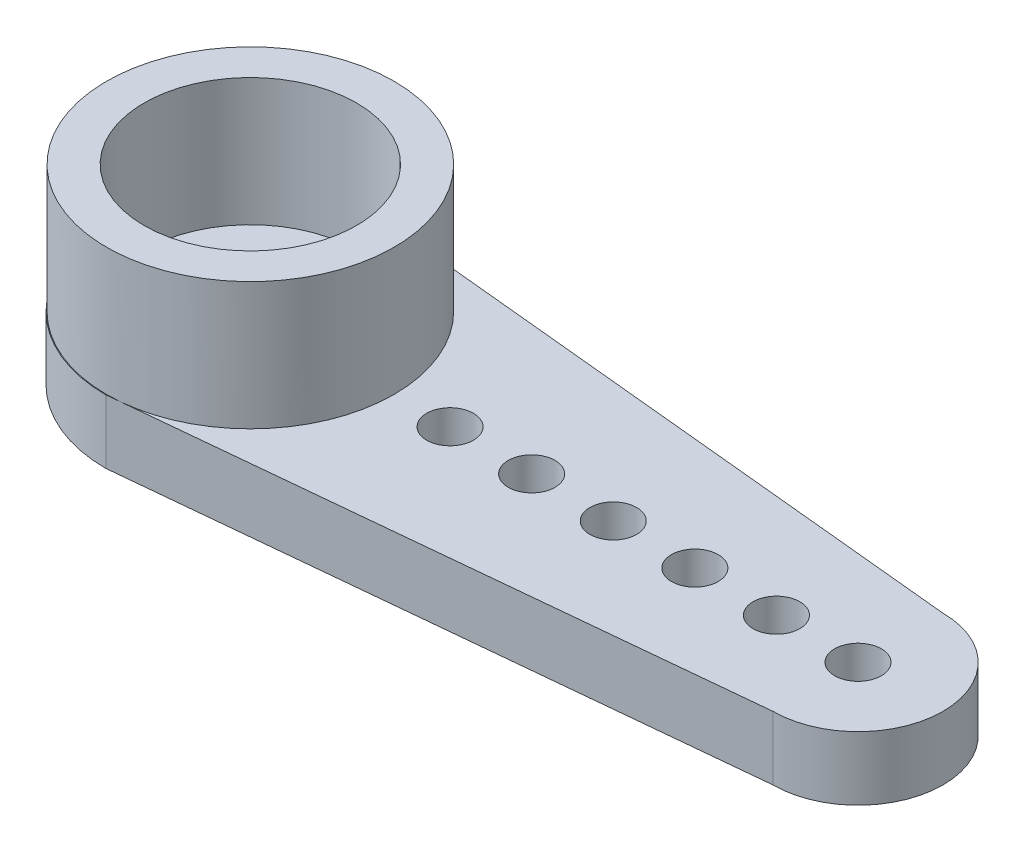
SolidWorks part; units mm, degrees
ref_plane "Front Plane" through (0, 0, 0) normal (0, 0, 1) x (1, 0, 0)
ref_plane "Top Plane" through (0, 0, 0) normal (0, 1, 0) x (1, 0, 0)
ref_plane "Right Plane" through (0, 0, 0) normal (1, 0, 0) x (0, 0, -1)
sketch "Sketch1" plane through (0, 0, 0) normal (0, 1, 0) x (1, 0, 0)
  line L1 (0, 3.4) -> (14.3, 2)
  line L2 (0, -3.4) -> (14.3, -2)
  arc A0 (0.6594, 3.3354) -> (0.6594, -3.3354) centre (0, 0) ccw
  arc A1 (14.3, -2) -> (14.3, 2) centre (14.3, 0) ccw
  dimension "D1" = 6.8
  dimension "D2" = 4
extrude "Boss-Extrude1" add sketch "Sketch1" along normal blind 1.5 contours L2 A1 L1 A0
sketch "Sketch2" plane through (0, 0, 0) normal (0, -1, 0) x (1, 0, 0)
  circle A0 centre (0, 0) radius 3.3838
extrude "Boss-Extrude2" add sketch "Sketch2" against normal blind 4.5
sketch "Sketch3" plane through (0, 4.5, 0) normal (0, 1, 0) x (1, 0, 0)
  circle A0 centre (0, 0) radius 2.5
  dimension "D1" = 5
extrude "Cut-Extrude1" cut sketch "Sketch3" against normal up to surface (3 mm away) up to face at (8.5784, 1.5, 0)
sketch "Sketch4" plane through (0, 1.5, 0) normal (0, 1, 0) x (1, 0, 0)
  circle A0 centre (0, 0) radius 1
  dimension "D1" = 2
extrude "Cut-Extrude2" cut sketch "Sketch4" against normal blind 3.5
sketch "Sketch5" plane through (0, 0, 0) normal (0, -1, 0) x (1, 0, 0)
  line L0 (14.85, 0) -> (4.15, 0) construction
  circle A0 centre (14.3, 0) radius 0.55
  arc A1 (14.3, -2) -> (14.3, 2) centre (14.3, 0) ccw construction
  circle A2 centre (12.38, 0) radius 0.55
  circle A3 centre (10.46, 0) radius 0.55
  circle A4 centre (8.54, 0) radius 0.55
  circle A5 centre (6.62, 0) radius 0.55
  circle A6 centre (4.7, 0) radius 0.55
  dimension "D1" = 1.1
  dimension "D3" = 10.7
  dimension "D2" = 6
extrude "Cut-Extrude3" cut sketch "Sketch5" against normal blind 3.5
scale "Scale1" scale about centroid uniform scaling yes scale factor 2
